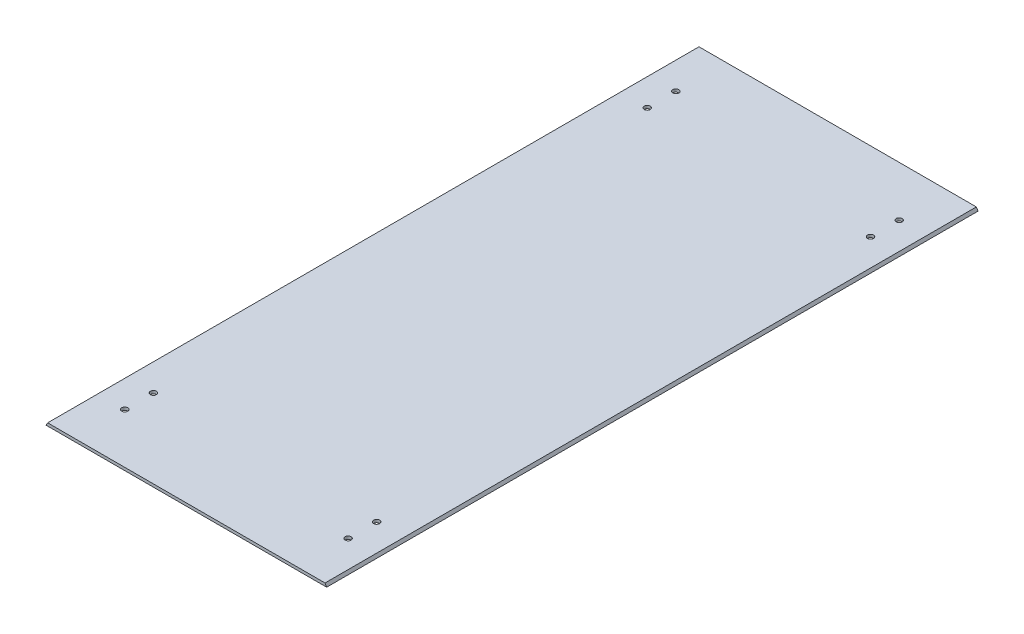
SolidWorks part; units mm, degrees
ref_plane "前视基准面" through (0, 0, 0) normal (0, 0, 1) x (1, 0, 0)
ref_plane "上视基准面" through (0, 0, 0) normal (0, 1, 0) x (1, 0, 0)
ref_plane "右视基准面" through (0, 0, 0) normal (1, 0, 0) x (0, 0, -1)
other "Configuration Table"
sketch "草图2" plane through (0, 0, 0) normal (0, 0, 1) x (1, 0, 0)
  line L0 (-98, -1) -> (-96.8453, 1)
  line L1 (-98, -1) -> (98.07, -1)
  line L3 (-96.8453, 1) -> (96.9153, 1)
  line L5 (-98, -1) -> (96.9217, 0.989) construction
  line L6 (-96.8525, 0.9876) -> (98.07, -1) construction
  line L7 (98.07, -1) -> (96.9153, 1)
  point P0 (0, 0)
  dimension "D1" = 60
  dimension "D2" = 196.07
  dimension "D3" = 60
  dimension "D4" = 2
  dimension "D5" = 1
extrude "凸台-拉伸1" add sketch "草图2" against normal blind 455
sketch "草图3" plane through (0, -1, 0) normal (0, -1, 0) x (-1, 0, 0)
  line L0 (98, 0) -> (-98.07, 0) construction
  line L1 (98, 455) -> (98, 0) construction
  line L2 (0, 0) -> (0, 458.5279) construction
  line L3 (98, 227.5) -> (-98.07, 227.5) construction
  line L4 (-98.07, 455) -> (-98.07, 0) construction
  circle A0 centre (78, 35) radius 2.1
  circle A1 centre (78, 55) radius 2.1
  circle A2 centre (-78, 55) radius 2.1
  circle A3 centre (-78, 35) radius 2.1
  circle A4 centre (-78, 420) radius 2.1
  circle A5 centre (-78, 400) radius 2.1
  circle A6 centre (78, 400) radius 2.1
  circle A7 centre (78, 420) radius 2.1
  dimension "D1" = 20
  dimension "D2" = 20
  dimension "D3" = 20
  dimension "D4" = 35
extrude "切除-拉伸1" cut sketch "草图3" against normal through all
